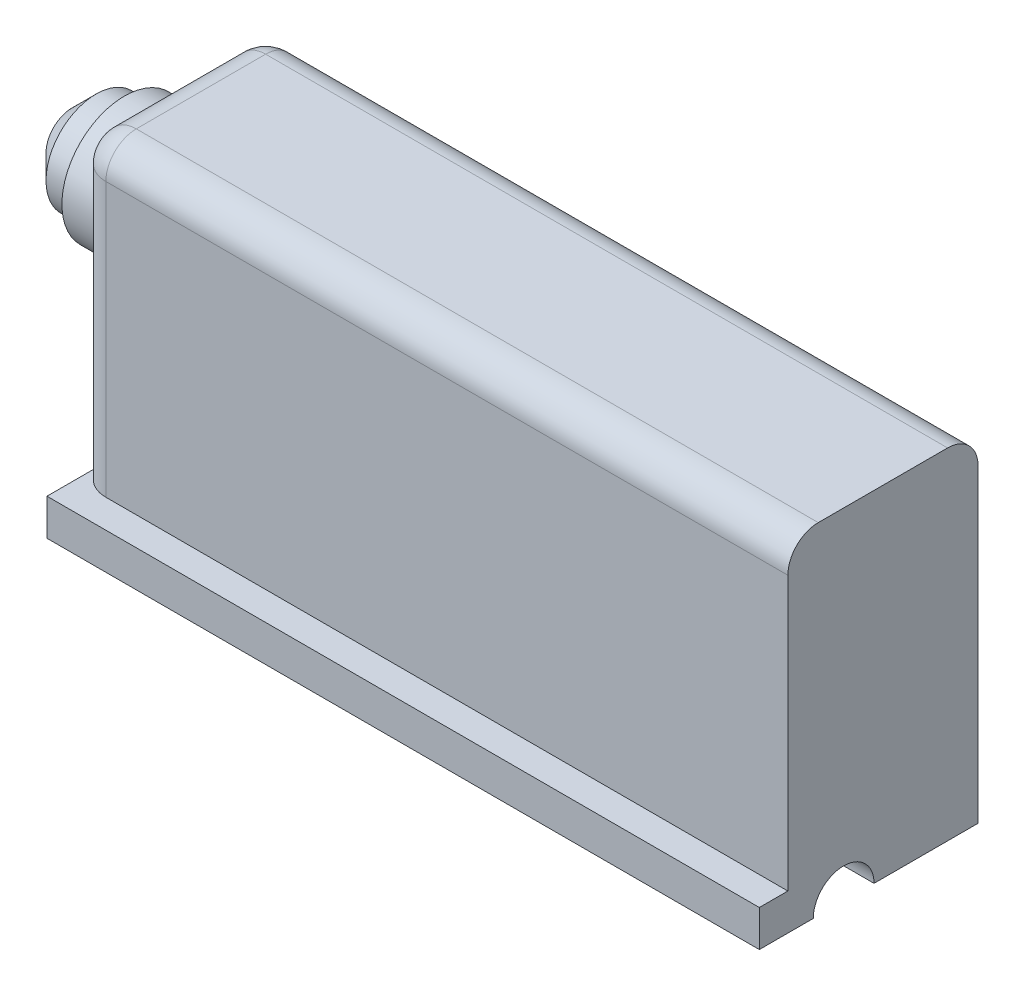
SolidWorks part; units mm, degrees
ref_plane "Front Plane" through (0, 0, 0) normal (0, 0, 1) x (1, 0, 0)
ref_plane "Top Plane" through (0, 0, 0) normal (0, 1, 0) x (1, 0, 0)
ref_plane "Right Plane" through (0, 0, 0) normal (1, 0, 0) x (0, 0, -1)
sketch "Sketch1" plane through (0, 0, 0) normal (0, 1, 0) x (1, 0, 0)
  line L1 (0, 0) -> (297.7363, 0)
  line L2 (0, 0) -> (0, 182.7784)
  line L3 (0, 182.7784) -> (297.7363, 182.7784)
  line L4 (297.7363, 0) -> (297.7363, 182.7784)
extrude "Boss-Extrude1" add sketch "Sketch1" along normal blind 15.24
sketch "Sketch2" plane through (0, 0, 0) normal (-1, 0, 0) x (0, 0, 1)
  line L0 (-139.3241, 0) -> (-113.9241, 0)
  line L1 (-182.7784, 0) -> (-139.3241, 0)
  line L2 (-182.7784, 0) -> (0, 0) construction
  line L3 (-91.3892, 0) -> (-91.3892, 15.24) construction
  line L4 (-182.7784, 15.24) -> (0, 15.24) construction
  line L5 (-139.3241, 0) -> (-126.6241, 0)
  line L6 (-43.4543, 0) -> (-68.8543, 0)
  arc A0 (-113.9241, 0) -> (-139.3241, 0) centre (-126.6241, 0) ccw
  arc A1 (-68.8543, 0) -> (-43.4543, 0) centre (-56.1543, 0) cw
  line M4 (-182.7784, 0) -> (0, 0)
extrude "Cut-Extrude1" cut sketch "Sketch2" against normal through all contours A1 M4 | L0 A0 M4
sketch "Sketch4" plane through (0, 0, 0) normal (-1, 0, 0) x (0, 0, 1)
  line L0 (-113.9241, 0) -> (-68.8543, 0) construction
  line L6 (-91.3892, 0) -> (0, 0)
  line L9 (-91.3892, 0) -> (-91.3892, 15.24)
  line L10 (-91.3892, 15.24) -> (0, 15.24)
  line L11 (0, 0) -> (0, 15.24)
  point P0 (-91.3892, 0)
extrude "Cut-Extrude3" cut sketch "Sketch4" against normal through all
sketch "Sketch5" plane through (0, 15.24, 0) normal (0, 1, 0) x (1, 0, 0)
  line L0 (297.7363, 91.3892) -> (297.7363, 182.7784) construction
  line L1 (0, 182.7784) -> (297.7363, 182.7784)
  line L2 (0, 182.7784) -> (0, 103.3111)
  line L3 (0, 103.3111) -> (297.7363, 103.3111)
  line L4 (297.7363, 182.7784) -> (297.7363, 103.3111)
extrude "Boss-Extrude2" add sketch "Sketch5" along normal blind 127
fillet "Fillet1" radius 12.7 1 edges at (148.8681, 142.24, -103.3111)
fillet "Fillet2" radius 12.7 1 edges at (148.8681, 142.24, -182.7784)
fillet "Fillet3" radius 12.7 5 edges at (0, 72.39, -103.3111) (0, 138.5203, -107.0309) (0, 64.77, -182.7784) (0, 142.24, -143.0448) (0, 138.5203, -179.0587)
sketch "Sketch6" plane through (0, 0, 0) normal (-1, 0, 0) x (0, 0, 1)
  line L0 (-143.0448, 142.24) -> (-143.0448, 0) construction
  line L1 (-170.0784, 142.24) -> (-116.0111, 142.24) construction
  line L2 (-170.0784, 0) -> (-139.3241, 0) construction
  line L3 (-143.0448, 0) -> (-143.0448, 98.4907) construction
  line L4 (-143.0448, 98.4907) -> (-170.0784, 98.4907) construction
  line L5 (-170.0784, 129.54) -> (-170.0784, 0) construction
  circle A0 centre (-143.0448, 98.4907) radius 26.1045
extrude "Boss-Extrude3" add sketch "Sketch6" along normal blind 19.304
sketch "Sketch7" plane through (-19.304, 0, 0) normal (-1, 0, 0) x (0, 0, 1)
  line L0 (-143.0448, 124.5952) -> (-143.0448, 98.4907) construction
  circle A0 centre (-143.0448, 98.4907) radius 26.1045 construction
  circle A1 centre (-143.0448, 98.4907) radius 26.1045 construction
  circle A2 centre (-143.0448, 98.4907) radius 20.9137
extrude "Boss-Extrude4" add sketch "Sketch7" along normal blind 21.844
chamfer "Chamfer1" distance 10 angle 45 1 edges at (-41.148, 98.4907, -122.1311)
sketch "Sketch8" plane through (-41.148, 0, 0) normal (-1, 0, 0) x (0, 0, 1)
  line L1 (-150.1448, 100.7277) -> (-152.0821, 99.6092)
  line L2 (-152.0821, 99.6092) -> (-152.0821, 97.3722)
  line L3 (-152.0821, 97.3722) -> (-150.1448, 96.2536)
  line L4 (-150.1448, 96.2536) -> (-148.2074, 97.3722)
  line L5 (-148.2074, 97.3722) -> (-148.2074, 99.6092)
  line L6 (-148.2074, 99.6092) -> (-150.1448, 100.7277)
  circle A0 centre (-143.0448, 98.4907) radius 4.3764
  circle A1 centre (-150.1448, 98.4907) radius 1.9373 construction
extrude "Cut-Extrude4" cut sketch "Sketch8" against normal blind 21.844
